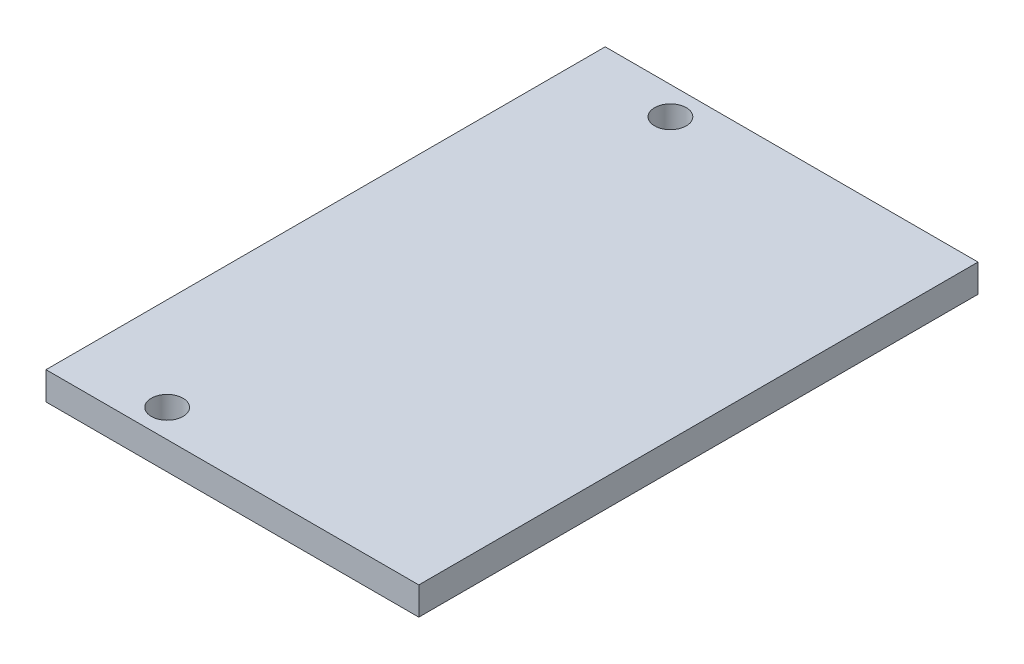
SolidWorks part; units mm, degrees
ref_plane "Front Plane" through (0, 0, 0) normal (0, 0, 1) x (1, 0, 0)
ref_plane "Top Plane" through (0, 0, 0) normal (0, 1, 0) x (1, 0, 0)
ref_plane "Right Plane" through (0, 0, 0) normal (1, 0, 0) x (0, 0, -1)
sketch "Sketch1" plane through (0, 0, 0) normal (0, 1, 0) x (1, 0, 0)
  line L0 (-55, 0) -> (55, 0) construction
  line L2 (-10, 30) -> (30, 30)
  line L3 (-10, 30) -> (-10, -30)
  line L4 (-10, -30) -> (30, -30)
  line L5 (30, 30) -> (30, -30)
  circle A0 centre (0, 27) radius 1.7
  circle A1 centre (0, -27) radius 1.7
  point P11 (-10, 0)
  dimension "D1" = 3.4
  dimension "D2" = 27
  dimension "D3" = 10
  dimension "D4" = 60
  dimension "D5" = 40
extrude "Boss-Extrude1" add sketch "Sketch1" along normal blind 3 contours L5 L2 L3 L4 A0 A1
